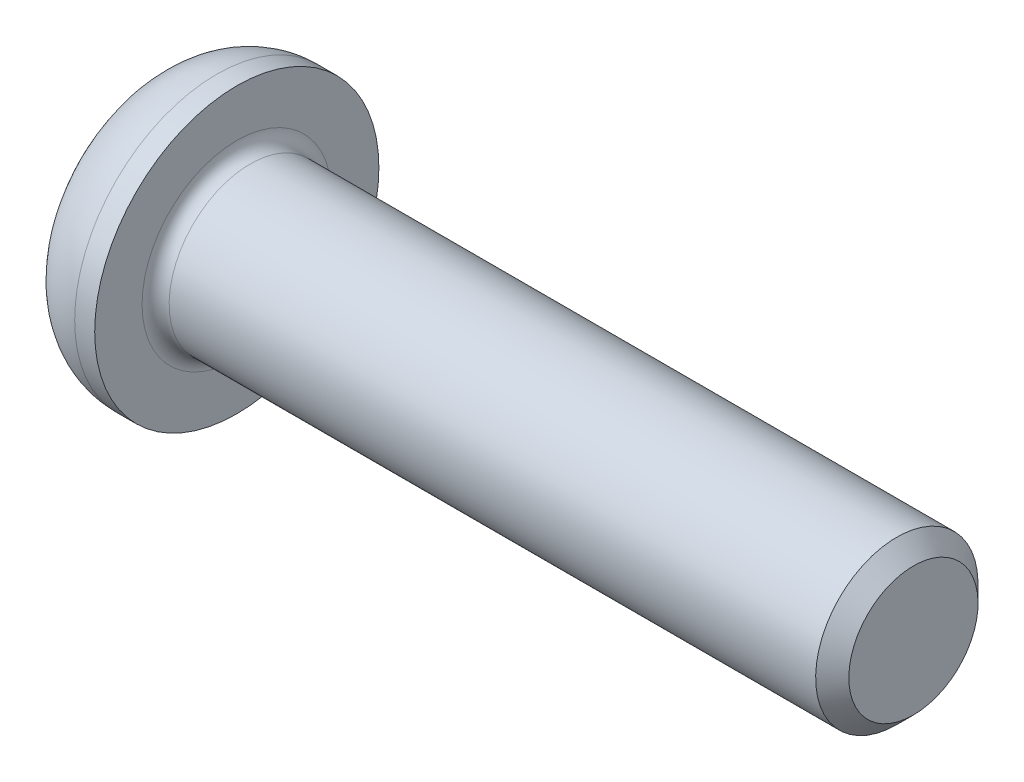
SolidWorks part; units mm, degrees
ref_plane "前基準面" through (0, 0, 0) normal (0, 0, 1) x (1, 0, 0)
ref_plane "上基準面" through (0, 0, 0) normal (0, 1, 0) x (1, 0, 0)
ref_plane "右基準面" through (0, 0, 0) normal (1, 0, 0) x (0, 0, -1)
ref_plane "平面1"
sketch "草圖1" plane through (0, 0, 0) normal (0, 0, 1) x (1, 0, 0)
  line L0 (0.1133, 0) -> (25, 0)
  line L1 (25, 0) -> (25, 3)
  line L2 (25, 3) -> (3, 3)
  line L3 (3, 3) -> (2.3864, 3)
  line L4 (2.3864, 3) -> (0, 3)
  line L5 (0, 3) -> (0, 5.25)
  line L6 (0, 5.25) -> (-3.3, 5.25)
  line L7 (-3.3, 5.25) -> (-3.3, 2.3094)
  line L8 (-3.3, 2.3094) -> (-1.22, 2.3094)
  line L9 (-1.22, 2.3094) -> (0.1133, 0)
  line L10 (0.1133, 0) -> (25, 0) construction
  dimension "D1" = 90
  dimension "D2" = 0.6135
  dimension "D3" = 3.3
  dimension "D4" = 2.08
  dimension "D5" = 120
  dimension "D6" = 3
  dimension "D7" = 3
  dimension "D8" = 2.3094
  dimension "D9" = 5.25
revolve "本體" add sketch "草圖1" angle 360 about L10
cosmetic thread "裝飾螺紋線1" parameters "D1"=22, "D2"=4.891
ref_plane "平面2"
sketch "草圖2" plane through (-3.3, 0, 0) normal (-1, 0, 0) x (0, 0, 1)
  line L0 (2.3094, 0) -> (1.1547, -2)
  line L1 (1.1547, -2) -> (-1.1547, -2)
  line L2 (-1.1547, -2) -> (-2.3094, 0)
  line L3 (-2.3094, 0) -> (-1.1547, 2)
  line L4 (-1.1547, 2) -> (1.1547, 2)
  line L5 (1.1547, 2) -> (2.3094, 0)
  circle A0 centre (0, 0) radius 2.3094
extrude "塞槽" add sketch "草圖2" against normal up to next contours A0 | L0 L1 L2 L3 L4 L5
fillet "螺紋" radius 2.56 1 edges at (-3.3, -5.25, 0)
chamfer "倒角1" distance 0.6135 distance2 0.6135 1 edges at (25, -3, 0)
fillet "圓角2" radius 0.5 1 edges at (0, -3, 0)
